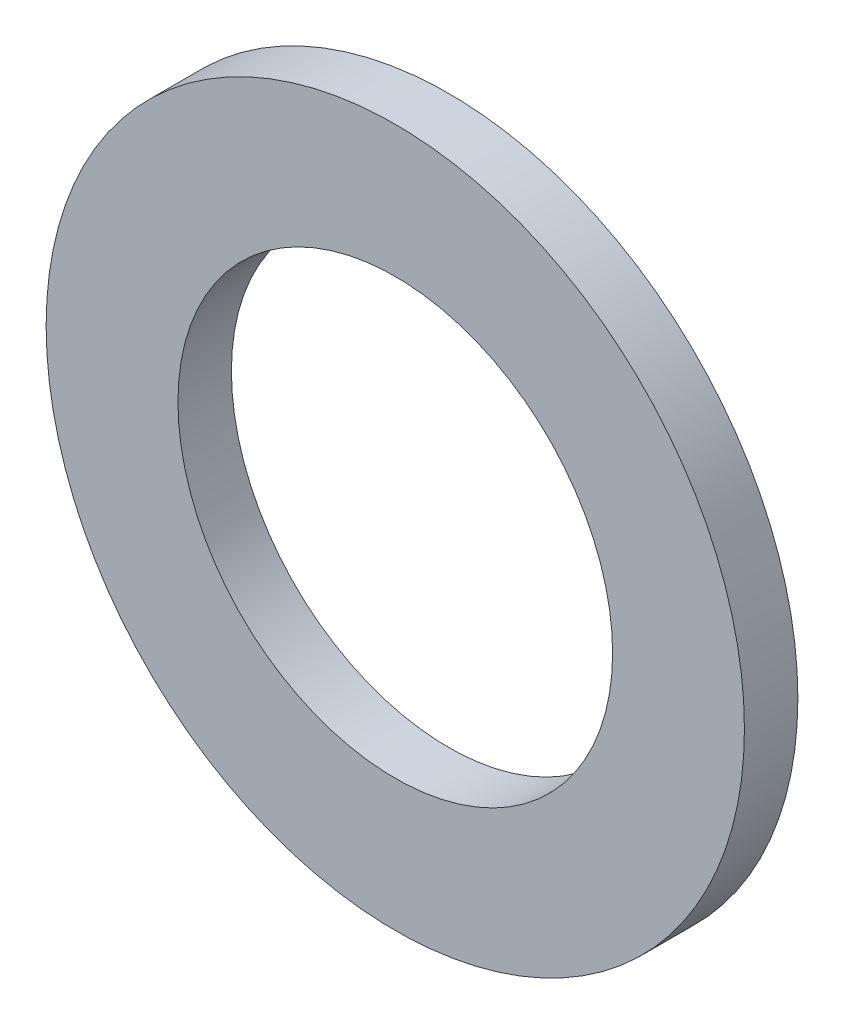
SolidWorks part; units mm, degrees
ref_plane "Plan de face" through (0, 0, 0) normal (0, 0, 1) x (1, 0, 0)
ref_plane "Plan de dessus" through (0, 0, 0) normal (0, 1, 0) x (1, 0, 0)
ref_plane "Plan de droite" through (0, 0, 0) normal (1, 0, 0) x (0, 0, -1)
sketch "Esquisse1" plane through (0, 0, 0) normal (0, 0, 1) x (1, 0, 0)
  circle A0 centre (0, 0) radius 9.8 construction
  circle A1 centre (0, 0) radius 9.8
  circle A2 centre (0, 0) radius 6.1 construction
  circle A3 centre (0, 0) radius 6.1
extrude "Extrusion1" add sketch "Esquisse1" along normal up to surface (1.5 mm away)
